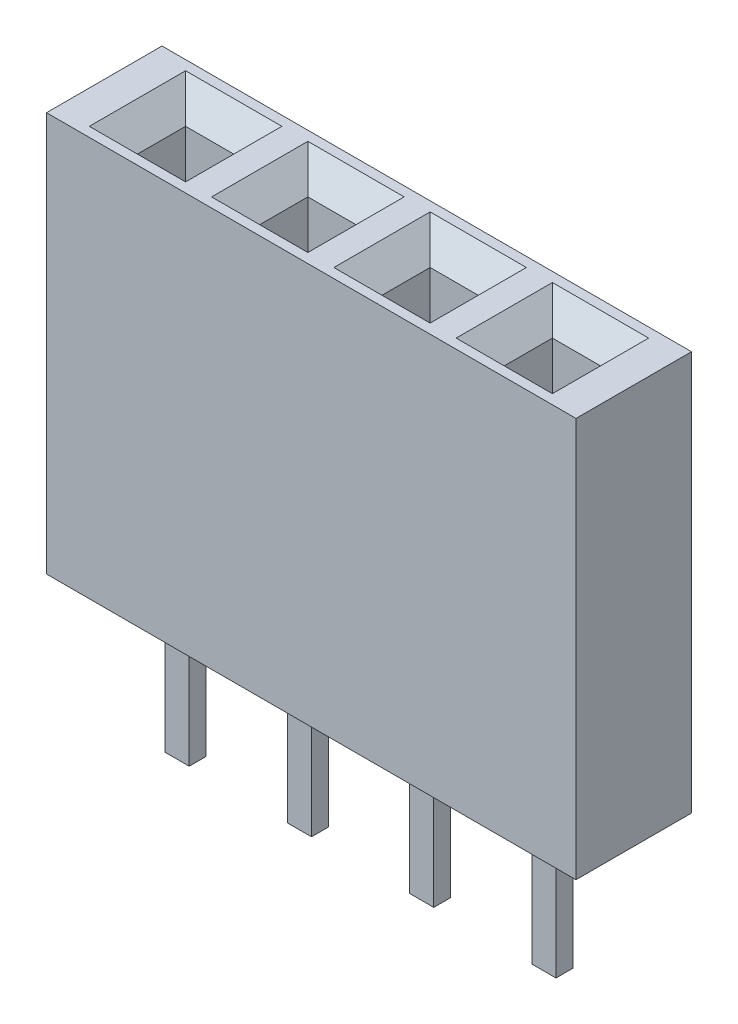
SolidWorks part; units mm, degrees
ref_plane "Front Plane" through (0, 0, 0) normal (0, 0, 1) x (1, 0, 0)
ref_plane "Top Plane" through (0, 0, 0) normal (0, 1, 0) x (1, 0, 0)
ref_plane "Right Plane" through (0, 0, 0) normal (1, 0, 0) x (0, 0, -1)
sketch "Sketch3" plane through (0, 0, 0) normal (0, 0, 1) x (1, 0, 0)
  line L1 (-5.5, -4.15) -> (5.5, -4.15)
  line L2 (-5.5, -4.15) -> (-5.5, 4.15)
  line L3 (-5.5, 4.15) -> (5.5, 4.15)
  line L4 (5.5, -4.15) -> (5.5, 4.15)
  line L5 (-5.5, -4.15) -> (5.5, 4.15) construction
  line L6 (-5.5, 4.15) -> (5.5, -4.15) construction
  point P0 (0, 0)
  dimension "D1" = 11
  dimension "D2" = 8.3
extrude "Boss-Extrude1" add sketch "Sketch3" along normal blind 2.4
sketch "Sketch5" plane through (0, 4.15, 0) normal (0, 1, 0) x (1, 0, 0)
  line L0 (-5.5, -2.4) -> (-5.5, 0) construction
  line L1 (-4.31, -0.7) -> (-3.31, -0.7)
  line L2 (-4.31, -0.7) -> (-4.31, -1.7)
  line L3 (-4.31, -1.7) -> (-3.31, -1.7)
  line L4 (-3.31, -0.7) -> (-3.31, -1.7)
  line L5 (-4.31, -0.7) -> (-3.31, -1.7) construction
  line L6 (-4.31, -1.7) -> (-3.31, -0.7) construction
  line L7 (-1.77, -0.7) -> (-1.77, -1.7)
  line L8 (-1.77, -0.7) -> (-0.77, -0.7)
  line L9 (-0.77, -0.7) -> (-0.77, -1.7)
  line L10 (-1.77, -1.7) -> (-0.77, -1.7)
  line L11 (-1.77, -1.7) -> (-0.77, -0.7) construction
  line L12 (-1.77, -0.7) -> (-0.77, -1.7) construction
  line L13 (0.77, -0.7) -> (0.77, -1.7)
  line L14 (0.77, -0.7) -> (1.77, -0.7)
  line L15 (1.77, -0.7) -> (1.77, -1.7)
  line L16 (0.77, -1.7) -> (1.77, -1.7)
  line L17 (0.77, -1.7) -> (1.77, -0.7) construction
  line L18 (0.77, -0.7) -> (1.77, -1.7) construction
  line L19 (3.31, -0.7) -> (3.31, -1.7)
  line L20 (3.31, -0.7) -> (4.31, -0.7)
  line L21 (4.31, -0.7) -> (4.31, -1.7)
  line L22 (3.31, -1.7) -> (4.31, -1.7)
  line L23 (3.31, -1.7) -> (4.31, -0.7) construction
  line L24 (3.31, -0.7) -> (4.31, -1.7) construction
  line L25 (-1.27, -1.2) -> (1.27, -1.2) construction
  point P0 (-3.81, -1.2)
  point P8 (-5.5, -1.2)
  point P10 (-1.27, -1.2)
  point P15 (1.27, -1.2)
  point P20 (3.81, -1.2)
  point P25 (-0.9515, -1.7)
  point P26 (-1.4083, -1.2)
  point P29 (0, -1.2)
  dimension "D1" = 1
  dimension "D3" = 2.54
  dimension "D2" = 4
extrude "Cut-Extrude1" cut sketch "Sketch5" against normal blind 5
chamfer "Chamfer1" distance 0.5 angle 45 16 edges at (4.31, 4.15, 1.2) (3.81, 4.15, 1.7) (3.31, 4.15, 1.2) (3.81, 4.15, 0.7) (1.77, 4.15, 1.2) (1.27, 4.15, 1.7) (0.77, 4.15, 1.2) (1.27, 4.15, 0.7) (-0.77, 4.15, 1.2) (-1.27, 4.15, 1.7) (-1.77, 4.15, 1.2) (-1.27, 4.15, 0.7) (-3.81, 4.15, 1.7) (-4.31, 4.15, 1.2) (-3.31, 4.15, 1.2) (-3.81, 4.15, 0.7)
sketch "Sketch4" plane through (0, -4.15, 0) normal (0, -1, 0) x (1, 0, 0)
  line L0 (-1.52, 1.375) -> (-1.52, 1.025)
  line L1 (-4.06, 1.375) -> (-3.56, 1.375)
  line L2 (-4.06, 1.375) -> (-4.06, 1.025)
  line L3 (-4.06, 1.025) -> (-3.56, 1.025)
  line L4 (-3.56, 1.375) -> (-3.56, 1.025)
  line L5 (-4.06, 1.375) -> (-3.56, 1.025) construction
  line L6 (-4.06, 1.025) -> (-3.56, 1.375) construction
  line L7 (-1.52, 1.375) -> (-1.02, 1.375)
  line L8 (-1.02, 1.375) -> (-1.02, 1.025)
  line L9 (-1.52, 1.025) -> (-1.02, 1.025)
  line L10 (-1.52, 1.025) -> (-1.02, 1.375) construction
  line L11 (-1.52, 1.375) -> (-1.02, 1.025) construction
  line L12 (1.02, 1.375) -> (1.02, 1.025)
  line L13 (1.02, 1.375) -> (1.52, 1.375)
  line L14 (1.52, 1.375) -> (1.52, 1.025)
  line L15 (1.02, 1.025) -> (1.52, 1.025)
  line L16 (1.02, 1.025) -> (1.52, 1.375) construction
  line L17 (1.02, 1.375) -> (1.52, 1.025) construction
  line L18 (3.56, 1.375) -> (3.56, 1.025)
  line L19 (3.56, 1.375) -> (4.06, 1.375)
  line L20 (4.06, 1.375) -> (4.06, 1.025)
  line L21 (3.56, 1.025) -> (4.06, 1.025)
  line L22 (3.56, 1.025) -> (4.06, 1.375) construction
  line L23 (3.56, 1.375) -> (4.06, 1.025) construction
  line L24 (-1.27, 1.2) -> (1.27, 1.2) construction
  line L25 (-5.5, 2.4) -> (-5.5, 0) construction
  point P0 (-3.81, 1.2)
  point P5 (-1.27, 1.2)
  point P11 (1.27, 1.2)
  point P16 (3.81, 1.2)
  point P22 (0, 1.2)
  point P24 (0, 0)
  point P27 (-5.5, 1.2)
  dimension "D1" = 0.5
  dimension "D2" = 0.35
  dimension "D4" = 2.54
  dimension "D3" = 4
extrude "Boss-Extrude2" add sketch "Sketch4" along normal blind 3
